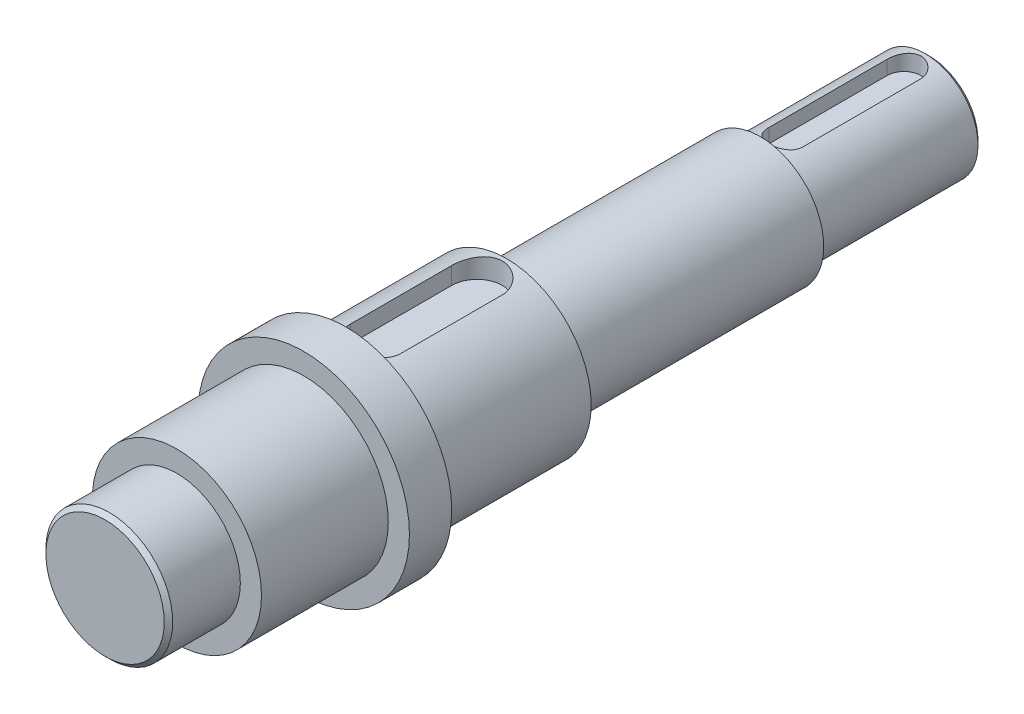
SolidWorks part; units mm, degrees
ref_plane "前视基准面" through (0, 0, 0) normal (0, 0, 1) x (1, 0, 0)
ref_plane "上视基准面" through (0, 0, 0) normal (0, 1, 0) x (1, 0, 0)
ref_plane "右视基准面" through (0, 0, 0) normal (1, 0, 0) x (0, 0, -1)
sketch "草图1" plane through (0, 0, 0) normal (0, 0, 1) x (1, 0, 0)
  circle A0 centre (0, 0) radius 12.5
extrude "凸台-拉伸1" add sketch "草图1" along normal blind 40
sketch "草图2" plane through (0, 0, 40) normal (0, 0, 1) x (1, 0, 0)
  circle A0 centre (0, 0) radius 15
extrude "凸台-拉伸2" add sketch "草图2" along normal blind 60
sketch "草图3" plane through (0, 0, 100) normal (0, 0, 1) x (1, 0, 0)
  circle A0 centre (0, 0) radius 20
extrude "凸台-拉伸3" add sketch "草图3" along normal blind 38
sketch "草图4" plane through (0, 0, 138) normal (0, 0, 1) x (1, 0, 0)
  circle A0 centre (0, 0) radius 25
extrude "凸台-拉伸4" add sketch "草图4" along normal blind 10
sketch "草图5" plane through (0, 0, 148) normal (0, 0, 1) x (1, 0, 0)
  circle A0 centre (0, 0) radius 20
extrude "凸台-拉伸5" add sketch "草图5" along normal blind 30
sketch "草图6" plane through (0, 0, 178) normal (0, 0, 1) x (1, 0, 0)
  circle A0 centre (0, 0) radius 15
extrude "凸台-拉伸6" add sketch "草图6" along normal blind 17
chamfer "倒角1" distance 1 distance2 1 1 edges at (15, 0, 195)
chamfer "倒角2" distance 1 distance2 1 1 edges at (12.5, 0, 0)
ref_plane "基准面1" through (0, 15, 0) normal (0, 1, 0) x (1, 0, 0)
sketch "草图7" plane through (0, 15, 0) normal (0, 1, 0) x (1, 0, 0)
  line L2 (-6, -131) -> (-6, -107)
  line L4 (6, -131) -> (6, -107)
  arc A0 (-6, -131) -> (6, -131) centre (0, -131) ccw
  arc A1 (6, -107) -> (-6, -107) centre (0, -107) ccw
extrude "切除-拉伸1" cut sketch "草图7" along normal blind 24
ref_plane "基准面2" through (0, 8.5, 0) normal (0, 1, 0) x (1, 0, 0)
sketch "草图8" plane through (0, 8.5, 0) normal (0, 1, 0) x (1, 0, 0)
  line L2 (-4, -6) -> (-4, -34)
  line L4 (4, -6) -> (4, -34)
  arc A0 (4, -6) -> (-4, -6) centre (0, -6) ccw
  arc A1 (-4, -34) -> (4, -34) centre (0, -34) ccw
extrude "切除-拉伸2" cut sketch "草图8" along normal blind 14
